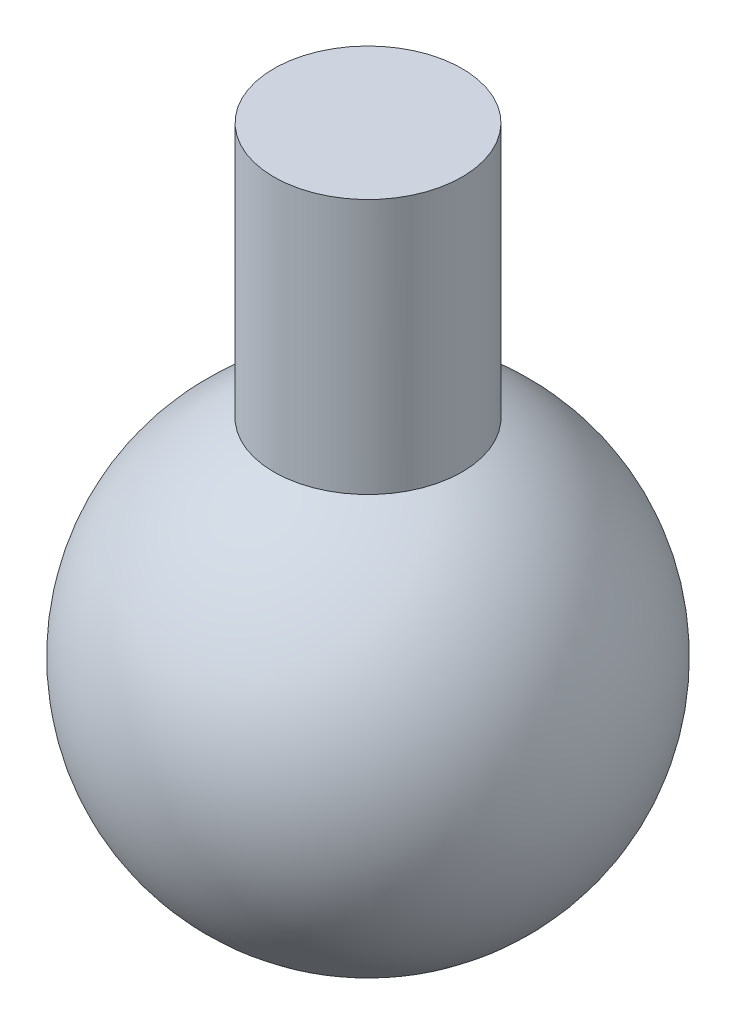
SolidWorks part; units mm, degrees
ref_plane "Front Plane" through (0, 0, 0) normal (0, 0, 1) x (1, 0, 0)
ref_plane "Top Plane" through (0, 0, 0) normal (0, 1, 0) x (1, 0, 0)
ref_plane "Right Plane" through (0, 0, 0) normal (1, 0, 0) x (0, 0, -1)
sketch "Sketch1" plane through (0, 0, 0) normal (0, 1, 0) x (1, 0, 0)
  line L0 (0, -29) -> (0, 29)
  arc A0 (0, -29) -> (0, 29) centre (0, 0) ccw
  dimension "D1" = 58
ref_plane "Plane1" through (0, 0, 0) normal (0, 1, 0) x (1, 0, 0)
revolve "Revolve1" add sketch "Sketch1" angle 360 about L0
ref_plane "Plane2" through (0, 29, 0) normal (0, 1, 0) x (1, 0, 0)
sketch "Sketch2" plane through (0, 29, 0) normal (0, 1, 0) x (1, 0, 0)
  circle A0 centre (0, 0) radius 12
extrude "Boss-Extrude1" add sketch "Sketch2" along normal blind 30 and the other way blind 6
